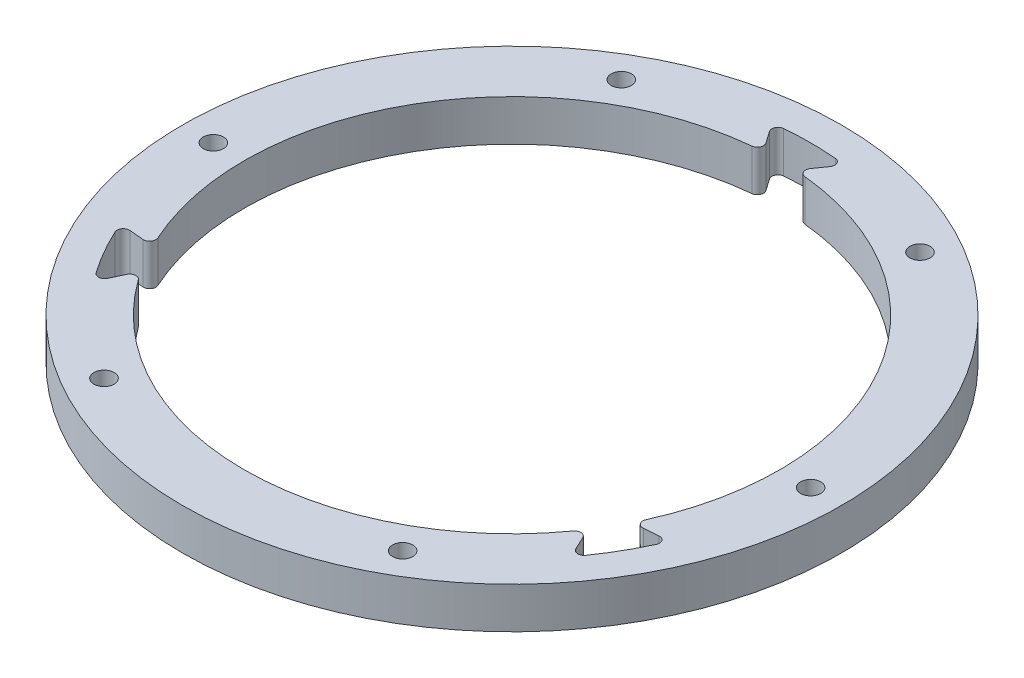
SolidWorks part; units mm, degrees
ref_plane "Front Plane" through (0, 0, 0) normal (0, 0, 1) x (1, 0, 0)
ref_plane "Top Plane" through (0, 0, 0) normal (0, 1, 0) x (1, 0, 0)
ref_plane "Right Plane" through (0, 0, 0) normal (1, 0, 0) x (0, 0, -1)
sketch "Sketch2" plane through (0, 0, 0) normal (1, 0, 0) x (0, 0, -1)
  line L0 (-65, 0) -> (-80, 0)
  line L1 (-80, 0) -> (-80, 10)
  line L2 (-80, 10) -> (-65, 10)
  line L5 (-65, 10) -> (-65, 0)
  point P3 (0, 0)
  point P6 (0, 0)
  point P8 (-21.7404, 0)
  point P9 (-22.787, 8.087)
  dimension "D1" = 80
  dimension "D2" = 10
  dimension "D4" = 15
ref_axis "Axis1" through (0, -0.75, 0) along (0, 1, 0)
revolve "Revolve1" add sketch "Sketch2" angle 360 about axis through (0, -0.75, 0) along (0, 1, 0)
sketch "Sketch4" plane through (0, 10, 0) normal (0, 1, 0) x (1, 0, 0)
  line L0 (0, 0) -> (0, 84.4218) construction
  line L1 (-3.8812, 64.884) -> (-8.8355, 71.9596)
  line L2 (8.8355, 71.9596) -> (3.8812, 64.884)
  line L3 (-3.8812, 64.884) -> (0, 59.3412) construction
  line L4 (0, 0) -> (-8.8355, 71.9596) construction
  arc A0 (-3.8812, 64.884) -> (3.8812, 64.884) centre (0, 0) cw
  arc A2 (-8.8355, 71.9596) -> (8.8355, 71.9596) centre (0, 0) cw
  circle A3 centre (0, 0) radius 65 construction
  dimension "D1" = 35
  dimension "D2" = 7.5
  dimension "D3" = 7
  dimension "D4" = 130
extrude "Cut-Extrude1" cut sketch "Sketch4" against normal through all
fillet "Fillet1" radius 1.5 4 edges at (8.8355, 5, -71.9596) (-8.8355, 5, -71.9596) (3.8812, 5, -64.884) (-3.8812, 5, -64.884)
pattern_circular "CirPattern2" count 3 over 360 about axis through (0, 0, 0) along (0, 1, 0) of "Cut-Extrude1", "Fillet1"
hole_wizard "#10 (0.1935) Diameter Hole1" positions "Sketch6" profile "Sketch7" hole size "#10" standard "ANSI Inch" end condition through all
sketch "Sketch6" plane through (0, 10, 0) normal (0, 1, 0) x (1, 0, 0)
  line L0 (0, 0) -> (-69.8201, 120.932) construction
  line L2 (0, 0) -> (0, 109.0908) construction
  point P0 (-36.25, 62.7868)
  dimension "D1" = 30
  dimension "D2" = 72.5
sketch "Sketch7" plane through (-36.25, 10, -62.7868) normal (1, 0, 0) x (0, 0, 1)
  line L0 (0, 0) -> (0, 10)
  line L1 (0, 10) -> (2.4574, 10)
  line L2 (2.4574, 10) -> (2.4574, 0)
  line L5 (2.4574, 0) -> (0, 0)
  line L11 (0, -6.35) -> (0, 107.95) construction
  dimension "Thru Hole Dia." = 4.9149
  dimension "Thru Hole Depth" = 10
pattern_circular "CirPattern3" count 6 over 360 about axis through (0, 0, 0) along (0, 1, 0) of "#10 (0.1935) Diameter Hole1"
